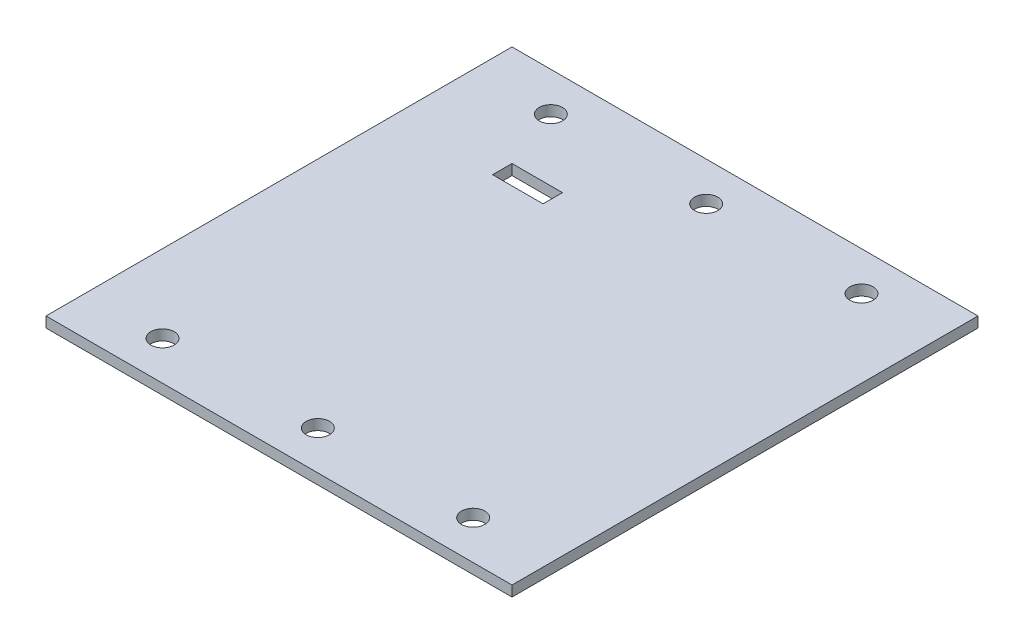
SolidWorks part; units mm, degrees
material "Acrílico (Impacto medio-alto)"
ref_plane "Alzado" through (0, 0, 0) normal (0, 0, 1) x (1, 0, 0)
ref_plane "Planta" through (0, 0, 0) normal (0, 1, 0) x (1, 0, 0)
ref_plane "Vista lateral" through (0, 0, 0) normal (1, 0, 0) x (0, 0, -1)
sketch "Croquis2" plane through (0, 0, 0) normal (0, 1, 0) x (1, 0, 0)
  line L1 (-60, -60) -> (60, -60)
  line L2 (-60, -60) -> (-60, 60)
  line L3 (-60, 60) -> (60, 60)
  line L4 (60, -60) -> (60, 60)
  line L5 (-60, -60) -> (60, 60) construction
  line L6 (-60, 60) -> (60, -60) construction
  point P0 (0, 0)
  dimension "D1" = 120
  dimension "D2" = 120
extrude "Saliente-Extruir2" add sketch "Croquis2" along normal blind 2.7
sketch "Croquis3" plane through (0, 2.7, 0) normal (0, 1, 0) x (1, 0, 0)
  line L0 (60, 60) -> (-60, 60) construction
  line L1 (0, 50) -> (40, 50) construction
  line L2 (0, 50) -> (-40, 50) construction
  line L3 (-60, 0) -> (60, 0) construction
  line L4 (-60, 60) -> (-60, -60) construction
  line L5 (60, -60) -> (60, 60) construction
  circle A0 centre (0, 50) radius 3
  circle A1 centre (40, 50) radius 3
  circle A2 centre (-40, 50) radius 3
  circle A3 centre (-40, -50) radius 3
  circle A4 centre (40, -50) radius 3
  circle A5 centre (0, -50) radius 3
  dimension "D1" = 6
  dimension "D2" = 10
  dimension "D4" = 40
  dimension "D6" = 40
  dimension "D3" = 2
  dimension "D5" = 2
extrude "Cortar-Extruir1" cut sketch "Croquis3" against normal through all
sketch "Croquis4" plane through (0, 0, 0) normal (0, -1, 0) x (1, 0, 0)
  line L0 (40, -40) -> (-40, -40) construction
  line L1 (-34, -34) -> (-21, -34)
  line L2 (-34, -34) -> (-34, -29)
  line L3 (-34, -29) -> (-21, -29)
  line L4 (-21, -34) -> (-21, -29)
  line L5 (-40, 40) -> (-40, -40) construction
  dimension "D1" = 13
  dimension "D2" = 5
  dimension "D3" = 6
  dimension "D4" = 6
extrude "Cortar-Extruir2" cut sketch "Croquis4" against normal blind 2.7
